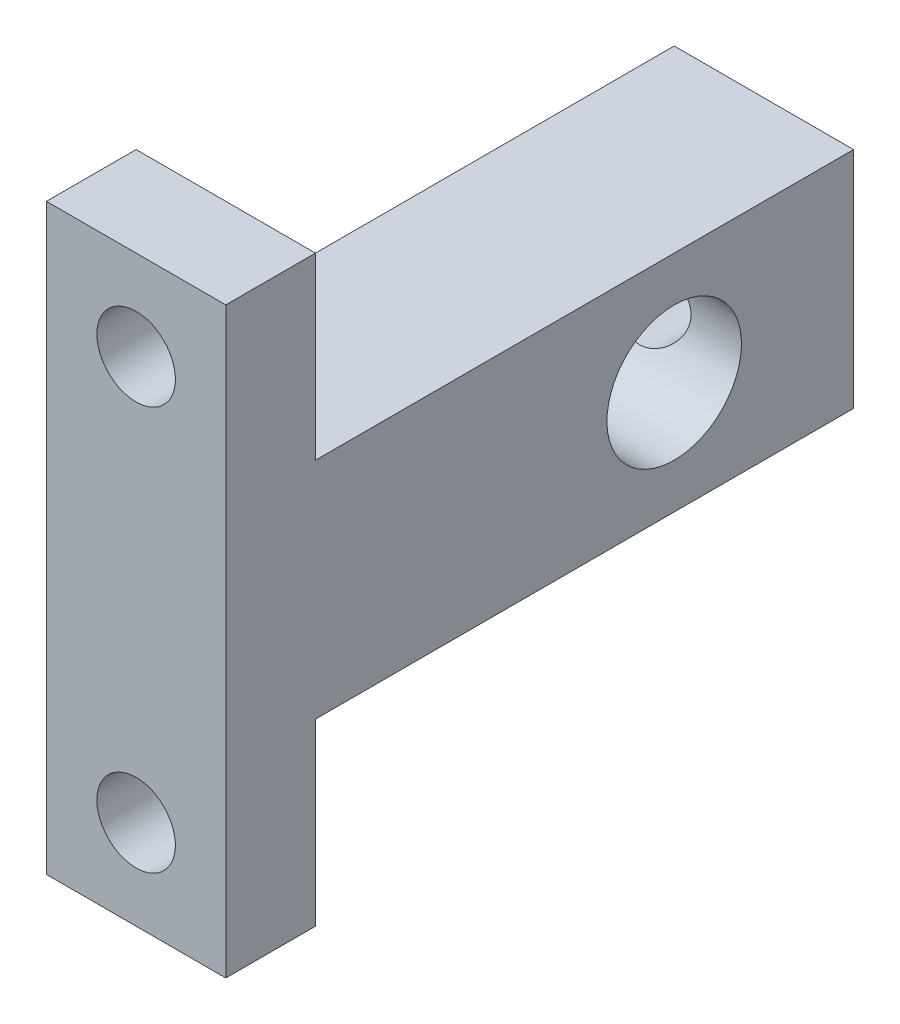
SolidWorks part; units mm, degrees
ref_plane "Front Plane" through (0, 0, 0) normal (0, 0, 1) x (1, 0, 0)
ref_plane "Top Plane" through (0, 0, 0) normal (0, 1, 0) x (1, 0, 0)
ref_plane "Right Plane" through (0, 0, 0) normal (1, 0, 0) x (0, 0, -1)
sketch "Sketch1" plane through (0, 0, 0) normal (0, 0, 1) x (1, 0, 0)
  line L1 (-4, 13) -> (4, 13)
  line L2 (-4, 13) -> (-4, -13)
  line L3 (-4, -13) -> (4, -13)
  line L4 (4, 13) -> (4, -13)
  line L5 (-4, 13) -> (4, -13) construction
  line L6 (-4, -13) -> (4, 13) construction
  point P0 (0, 0)
  dimension "D1" = 26
  dimension "D2" = 8
extrude "Boss-Extrude1" add sketch "Sketch1" along normal blind 4
sketch "Sketch2" plane through (0, 0, 0) normal (0, 0, -1) x (-1, 0, 0)
  line L0 (-4, 13) -> (4, 13) construction
  circle A0 centre (0, 9) radius 1.75
  circle A1 centre (0, -9) radius 1.75
  dimension "D1" = 3.5
  dimension "D2" = 3.5
  dimension "D3" = 4
  dimension "D4" = 18
extrude "Cut-Extrude1" cut sketch "Sketch2" against normal blind 4
sketch "Sketch3" plane through (0, 0, 0) normal (0, 0, -1) x (-1, 0, 0)
  line L1 (-4, 5) -> (4, 5)
  line L2 (-4, 5) -> (-4, -5)
  line L3 (-4, -5) -> (4, -5)
  line L4 (4, 5) -> (4, -5)
  line L5 (-4, 5) -> (4, -5) construction
  line L6 (-4, -5) -> (4, 5) construction
  point P0 (0, 0)
  dimension "D1" = 8
  dimension "D2" = 10
extrude "Boss-Extrude2" add sketch "Sketch3" along normal blind 24
sketch "Sketch4" plane through (4, 0, 0) normal (1, 0, 0) x (0, 0, -1)
  line L0 (-4, -13) -> (-4, 13) construction
  circle A0 centre (16, 0) radius 3
  dimension "D1" = 6
  dimension "D2" = 20
extrude "Cut-Extrude2" cut sketch "Sketch4" against normal blind 20
sketch "Sketch5" plane through (0, 0, -24) normal (0, 0, -1) x (-1, 0, 0)
  circle A0 centre (0, 0) radius 1.75
  dimension "D1" = 3.5
extrude "Cut-Extrude3" cut sketch "Sketch5" against normal up to surface (5 mm away)
